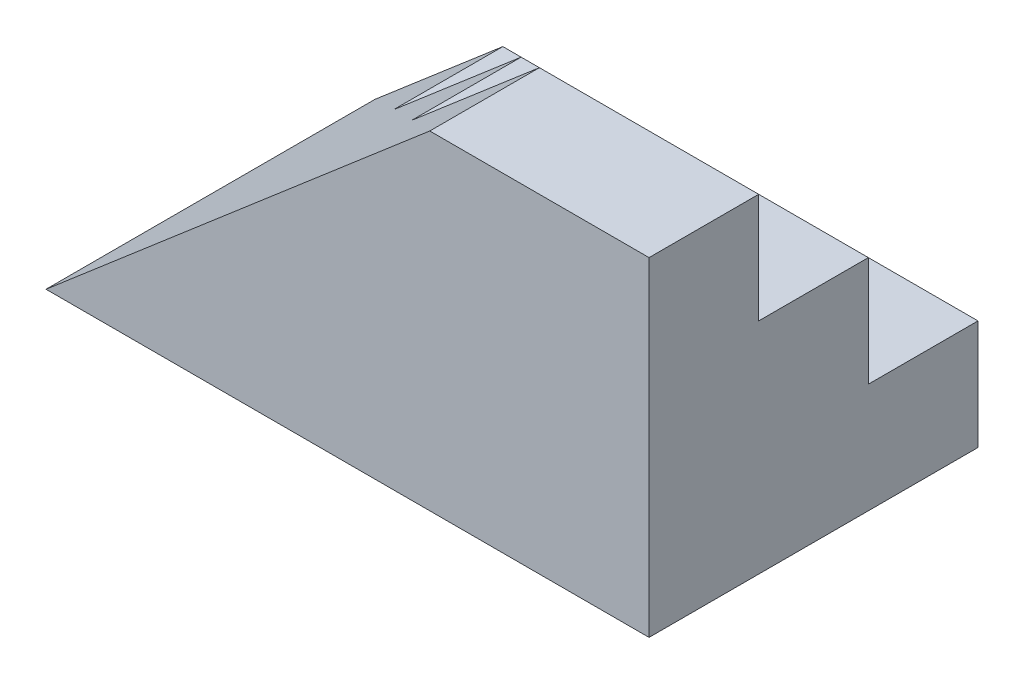
SolidWorks part; units mm, degrees
material "Ductile Iron"
ref_plane "Front Plane" through (0, 0, 0) normal (0, 0, 1) x (1, 0, 0)
ref_plane "Top Plane" through (0, 0, 0) normal (0, 1, 0) x (1, 0, 0)
ref_plane "Right Plane" through (0, 0, 0) normal (1, 0, 0) x (0, 0, -1)
sketch "Croquis2" plane through (0, 0, 0) normal (1, 0, 0) x (0, 0, -1)
  line L0 (0, 0) -> (60, 0)
  line L1 (60, 0) -> (60, 20)
  line L2 (60, 20) -> (40, 20)
  line L3 (40, 20) -> (40, 40)
  line L4 (40, 40) -> (20, 40)
  line L5 (20, 40) -> (20, 60)
  line L6 (20, 60) -> (0, 60)
  line L7 (0, 60) -> (0, 0)
  dimension "D1" = 60
  dimension "D2" = 20
  dimension "D3" = 20
  dimension "D4" = 20
  dimension "D5" = 20
  dimension "D6" = 20
  dimension "D7" = 20
extrude "Saliente-Extruir1" add sketch "Croquis2" along normal blind 110
sketch "Croquis3" plane through (0, 0, 0) normal (0, 0, 1) x (1, 0, 0)
  line L0 (0, 0) -> (70, 60)
  line L1 (110, 60) -> (0, 60) construction
  line L2 (110, 60) -> (110, 0) construction
  dimension "D1" = 40
extrude "Cortar-Extruir1" cut sketch "Croquis3" against normal through all and the other way through all
